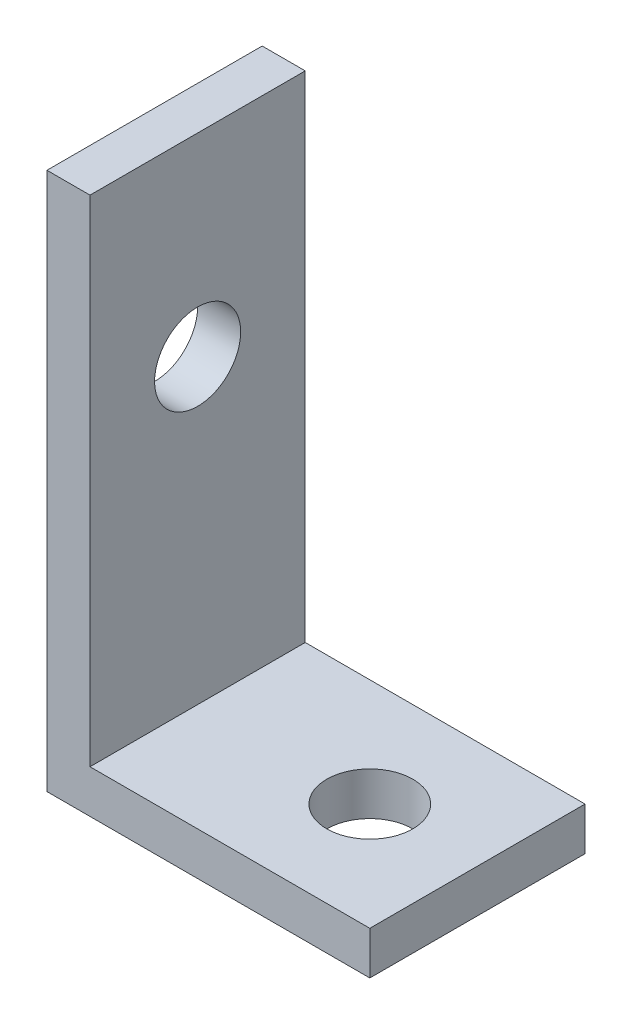
SolidWorks part; units mm, degrees
ref_plane "前视基准面" through (0, 0, 0) normal (0, 0, 1) x (1, 0, 0)
ref_plane "上视基准面" through (0, 0, 0) normal (0, 1, 0) x (1, 0, 0)
ref_plane "右视基准面" through (0, 0, 0) normal (1, 0, 0) x (0, 0, -1)
sketch "草图1" plane through (0, 0, 0) normal (0, 0, 1) x (1, 0, 0)
  line L0 (0, 0) -> (0, 25)
  line L1 (0, 25) -> (2, 25)
  line L2 (2, 25) -> (2, 2)
  line L3 (2, 2) -> (15, 2)
  line L4 (15, 2) -> (15, 0)
  line L5 (15, 0) -> (0, 0)
  dimension "D1" = 2
  dimension "D2" = 2
  dimension "D3" = 15
  dimension "D4" = 25
extrude "凸台-拉伸1" add sketch "草图1" along normal blind 10
sketch "草图2" plane through (0, 2, 0) normal (0, 1, 0) x (1, 0, 0)
  line L0 (15, 0) -> (2, 0) construction
  line L1 (15, -10) -> (15, 0) construction
  circle A0 centre (10, -5) radius 2
  dimension "D1" = 5
  dimension "D2" = 5
extrude "切除-拉伸1" cut sketch "草图2" against normal blind 10
sketch "草图3" plane through (2, 0, 0) normal (1, 0, 0) x (0, 0, -1)
  line L0 (0, 2) -> (0, 25) construction
  line L1 (-10, 25) -> (0, 25) construction
  circle A0 centre (-5, 16) radius 2
  dimension "D1" = 5
  dimension "D2" = 9
extrude "切除-拉伸2" cut sketch "草图3" against normal blind 10
